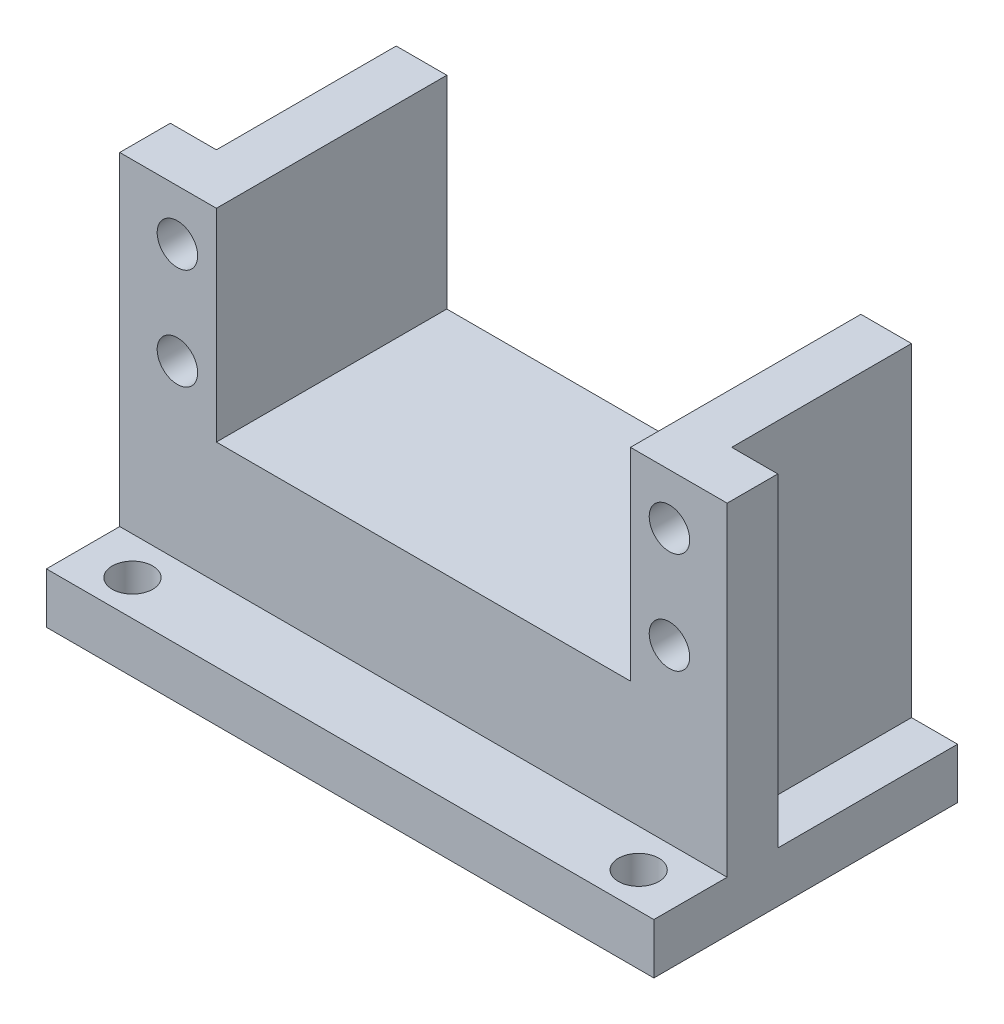
SolidWorks part; units mm, degrees
ref_plane "Front Plane" through (0, 0, 0) normal (0, 0, 1) x (1, 0, 0)
ref_plane "Top Plane" through (0, 0, 0) normal (0, 1, 0) x (1, 0, 0)
ref_plane "Right Plane" through (0, 0, 0) normal (1, 0, 0) x (0, 0, -1)
sketch "Sketch1" plane through (0, 0, 0) normal (0, 1, 0) x (1, 0, 0)
  line L1 (30, -15) -> (-30, -15)
  line L2 (30, -15) -> (30, 15)
  line L3 (30, 15) -> (-30, 15)
  line L4 (-30, -15) -> (-30, 15)
  line L5 (30, -15) -> (-30, 15) construction
  line L6 (30, 15) -> (-30, -15) construction
  point P0 (0, 0)
  dimension "D1" = 30
  dimension "D2" = 60
extrude "Boss-Extrude1" add sketch "Sketch1" along normal blind 5
sketch "Sketch3" plane through (0, 5, 0) normal (0, 1, 0) x (1, 0, 0)
  line L0 (30, 15) -> (-30, 15) construction
  line L1 (-20.45, -7.76) -> (-25.45, -7.76) construction
  line L2 (-20.45, -7.76) -> (-20.45, 15)
  line L3 (-20.45, 15) -> (-25.45, 15)
  line L4 (-25.45, -2.76) -> (-25.45, 15)
  line L5 (-20.45, -7.76) -> (-25.45, 15) construction
  line L6 (-20.45, 15) -> (-25.45, -7.76) construction
  line L7 (20.45, 3.62) -> (-20.45, 3.62)
  line L8 (25.45, -7.76) -> (20.45, -7.76) construction
  line L9 (25.45, -7.76) -> (25.45, 15) construction
  line L10 (25.45, 15) -> (20.45, 15) construction
  line L11 (20.45, -7.76) -> (20.45, 15) construction
  line L12 (25.45, -7.76) -> (20.45, 15) construction
  line L13 (25.45, 15) -> (20.45, -7.76) construction
  line L14 (-25.45, -2.76) -> (-30, -2.76)
  line L15 (-30, 15) -> (-30, -15) construction
  line L16 (-30, -2.76) -> (-30, -7.76)
  line L17 (-30, -7.76) -> (-20.45, -7.76)
  point P0 (-22.95, 3.62)
  point P7 (22.95, 3.62)
  point P16 (0, 3.62)
  dimension "D1" = 40.9
  dimension "D2" = 5
  dimension "D3" = 22.76
  dimension "D4" = 5
sketch "Sketch6" plane through (0, 5, 0) normal (0, 1, 0) x (1, 0, 0)
  line L0 (-20.45, 15) -> (-25.45, 15)
  line L1 (-25.45, 15) -> (-25.45, -2.76)
  line L2 (-25.45, -2.76) -> (-30, -2.76)
  line L3 (-30, -2.76) -> (-30, -7.76)
  line L4 (-30, -7.76) -> (-20.45, -7.76)
  line L5 (-20.45, -7.76) -> (-20.45, 15)
  line L6 (0, -2.75) -> (0, 2.75) construction
  line L7 (30, -2.76) -> (30, -7.76)
  line L8 (30, -7.76) -> (20.45, -7.76)
  line L9 (25.45, -2.76) -> (30, -2.76)
  line L10 (25.45, 15) -> (25.45, -2.76)
  line L11 (20.45, 15) -> (25.45, 15)
  line L12 (20.45, -7.76) -> (20.45, 15)
extrude "Boss-Extrude4" add sketch "Sketch6" along normal up to vertex (32 mm away)
sketch "Sketch7" plane through (0, 5, 0) normal (0, 1, 0) x (1, 0, 0)
  line L1 (20.45, 15) -> (-20.45, 15)
  line L2 (20.45, 15) -> (20.45, -7.76)
  line L3 (20.45, -7.76) -> (-20.45, -7.76)
  line L4 (-20.45, 15) -> (-20.45, -7.76)
extrude "Boss-Extrude5" add sketch "Sketch7" along normal up to vertex (12 mm away)
sketch "Sketch9" plane through (0, 5, 0) normal (0, 1, 0) x (1, 0, 0)
  line L0 (-30, -15) -> (30, -15) construction
  line L1 (30, -15) -> (30, -7.76) construction
  line L2 (-30, -7.76) -> (-30, -15) construction
  circle A0 centre (-25, -11.5) radius 2
  circle A1 centre (25, -11.5) radius 2
  dimension "D1" = 4
  dimension "D2" = 4
  dimension "D4" = 5
  dimension "D5" = 5
  dimension "D6" = 3.5
  dimension "D3" = 3.5
extrude "Cut-Extrude2" cut sketch "Sketch9" against normal up to surface (5 mm away) up to face at (0, 0, 0)
sketch "Sketch10" plane through (0, 0, 7.76) normal (0, 0, 1) x (1, 0, 0)
  line L2 (-30, 0) -> (30, 0) construction
  line L3 (-20.45, 37) -> (-20.45, 17) construction
  line L5 (0, -16.5) -> (0, 16.5) construction
  circle A0 centre (-24.3, 32) radius 2
  circle A1 centre (-24.3, 22) radius 2
  circle A3 centre (24.3, 22) radius 2
  circle A4 centre (24.3, 32) radius 2
  point P8 (0, 0)
  dimension "D3" = 4
  dimension "D1" = 22
  dimension "D2" = 10
  dimension "D4" = 3.85
  dimension "D5" = 3.85
extrude "Cut-Extrude3" cut sketch "Sketch10" against normal blind 4
